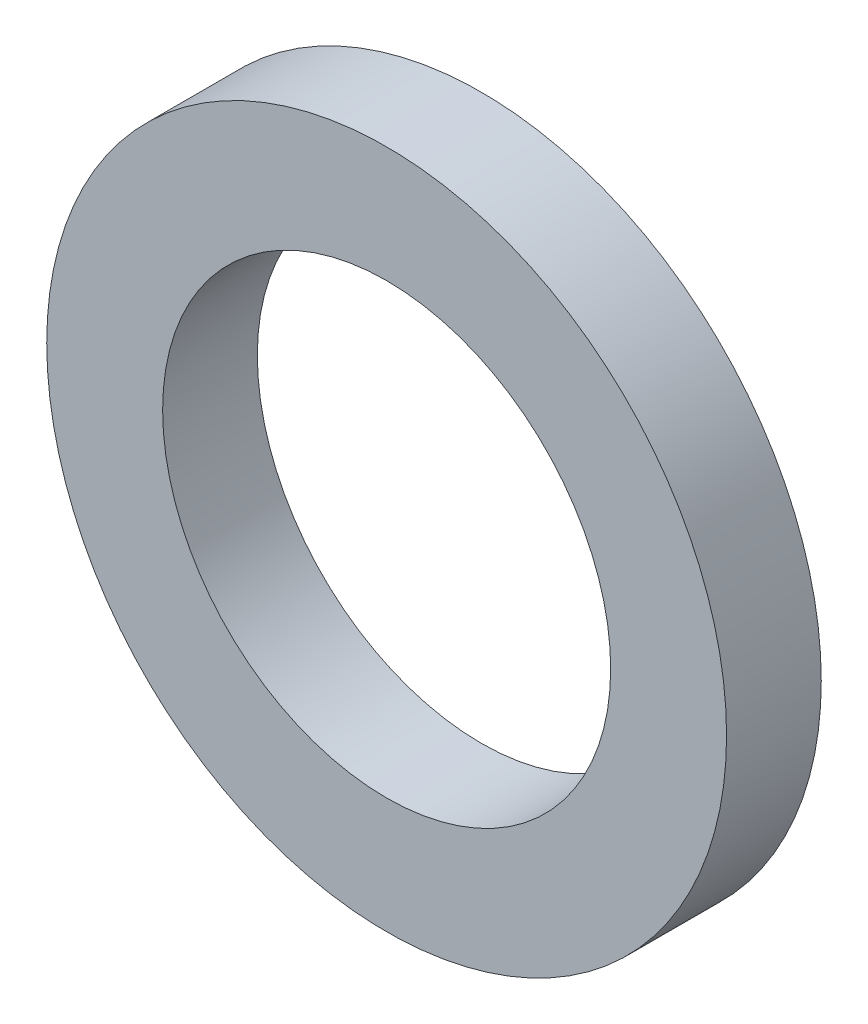
SolidWorks part; units mm, degrees
material "Rubber"
ref_plane "Front Plane" through (0, 0, 0) normal (0, 0, 1) x (1, 0, 0)
ref_plane "Top Plane" through (0, 0, 0) normal (0, 1, 0) x (1, 0, 0)
ref_plane "Right Plane" through (0, 0, 0) normal (1, 0, 0) x (0, 0, -1)
other "Configuration Table"
sketch "Sketch1" plane through (0, 0, 0) normal (0, 0, 1) x (1, 0, 0)
  circle A0 centre (0, 0) radius 12.2174
  circle A1 centre (0, 0) radius 8.0518
  dimension "D1" = 16.1036
  dimension "D2" = 24.4348
extrude "Boss-Extrude1" add sketch "Sketch1" against normal blind 3.4036
